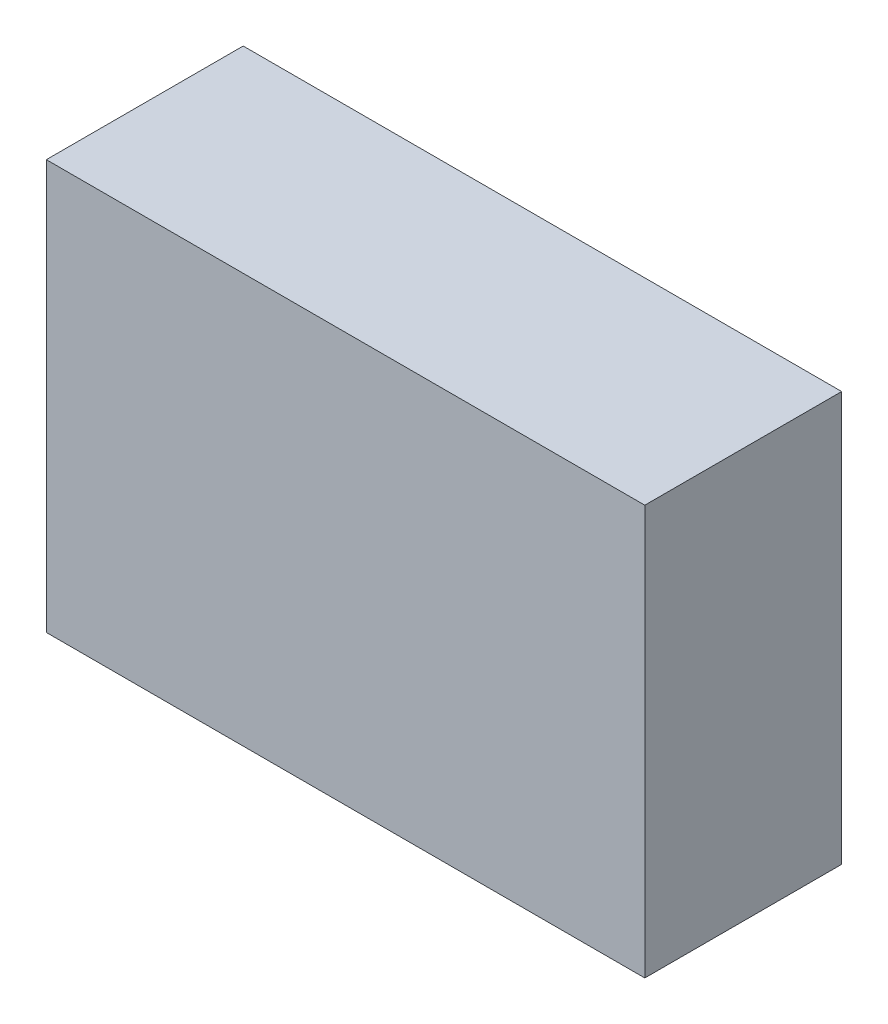
SolidWorks part; units mm, degrees
ref_plane "前视基准面" through (0, 0, 0) normal (0, 0, 1) x (1, 0, 0)
ref_plane "上视基准面" through (0, 0, 0) normal (0, 1, 0) x (1, 0, 0)
ref_plane "右视基准面" through (0, 0, 0) normal (1, 0, 0) x (0, 0, -1)
other "Configuration Table"
sketch "草图1" plane through (0, 0, 0) normal (0, 0, 1) x (1, 0, 0)
  line L0 (0, 0) -> (76, 0)
  line L1 (76, 0) -> (76, 52)
  line L2 (76, 52) -> (0, 52)
  line L3 (0, 52) -> (0, 0)
  dimension "width" = 76
  dimension "height" = 52
extrude "Fused_distribution_enclosure" add sketch "草图1" along normal blind 25
